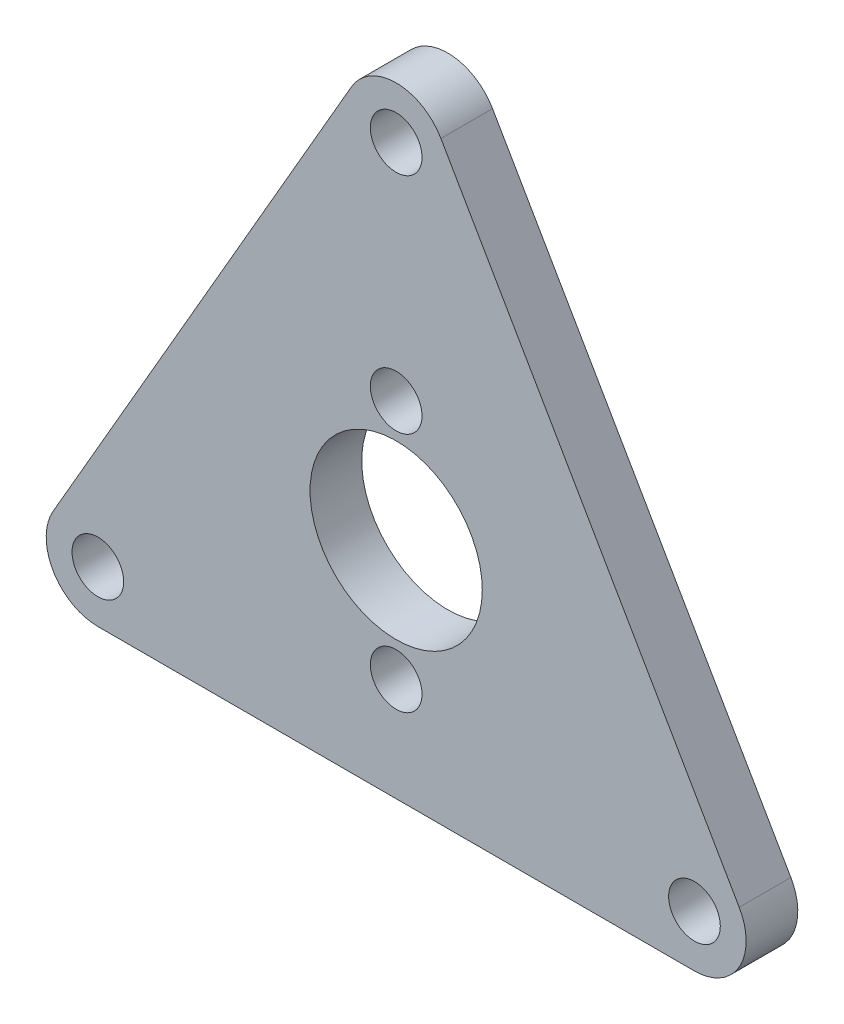
SolidWorks part; units mm, degrees
material "Thornel Mat VMA"
ref_plane "前视基准面" through (0, 0, 0) normal (0, 0, 1) x (1, 0, 0)
ref_plane "上视基准面" through (0, 0, 0) normal (0, 1, 0) x (1, 0, 0)
ref_plane "右视基准面" through (0, 0, 0) normal (1, 0, 0) x (0, 0, -1)
sketch "草图1" plane through (0, 0, 0) normal (0, 0, 1) x (1, 0, 0)
  line L0 (0, 20) -> (-17.3205, -10) construction
  line L1 (-17.3205, -10) -> (17.3205, -10) construction
  line L2 (17.3205, -10) -> (0, 20) construction
  line L3 (-2.5981, 21.5) -> (-19.9186, -8.5)
  line L4 (-17.3205, -13) -> (17.3205, -13)
  line L5 (19.9186, -8.5) -> (2.5981, 21.5)
  circle A0 centre (0, 0) radius 20 construction
  circle A1 centre (-17.3205, -10) radius 1.5
  circle A2 centre (0, 20) radius 1.5
  circle A3 centre (17.3205, -10) radius 1.5
  circle A4 centre (0, 0) radius 5
  circle A5 centre (0, 0) radius 7 construction
  circle A6 centre (0, 7) radius 1.5
  circle A7 centre (0, -7) radius 1.5
  circle A8 centre (0, 0) radius 26 construction
  arc A9 (-19.9186, -8.5) -> (-17.3205, -13) centre (-17.3205, -10) ccw
  arc A10 (17.3205, -13) -> (19.9186, -8.5) centre (17.3205, -10) ccw
  arc A11 (-2.5981, 21.5) -> (2.5981, 21.5) centre (0, 20) cw
  point P23 (-22.5167, -13)
  point P26 (22.5167, -13)
  point P29 (0, 26)
  dimension "D1" = 40
  dimension "D2" = 3
  dimension "D3" = 10
  dimension "D4" = 14
  dimension "D5" = 3
  dimension "D6" = 3
  dimension "D7" = 3
extrude "凸台-拉伸1" add sketch "草图1" along normal blind 3
